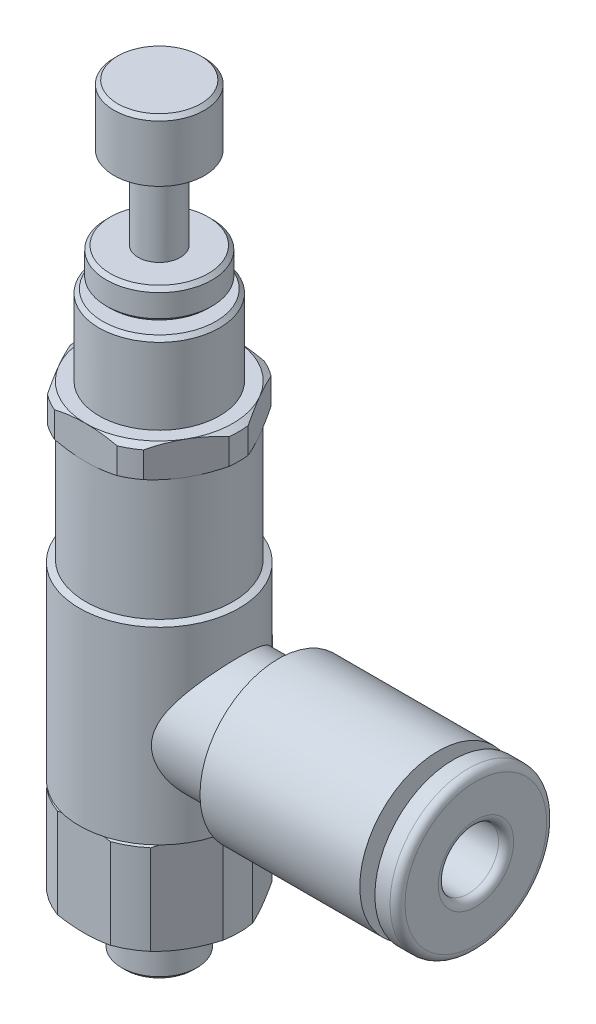
SolidWorks part; units mm, degrees
ref_plane "Front" through (0, 0, 0) normal (0, 0, 1) x (1, 0, 0)
ref_plane "Top" through (0, 0, 0) normal (0, 1, 0) x (1, 0, 0)
ref_plane "Right" through (0, 0, 0) normal (1, 0, 0) x (0, 0, -1)
ref_plane "K" through (0, 17.2, 0) normal (0, 1, 0) x (-1, 0, 0)
ref_plane "H" through (0, -15.5, 0) normal (0, 1, 0) x (-1, 0, 0)
ref_plane "J" through (0, 34.5, 0) normal (0, 1, 0) x (-1, 0, 0)
ref_plane "A" through (21, 0, 0) normal (1, 0, 0) x (0, 0, -1)
ref_plane "G" through (0, -12, 0) normal (0, 1, 0) x (-1, 0, 0)
ref_plane "Nut Thickness" through (0, -5.7, 0) normal (0, 1, 0) x (-1, 0, 0)
sketch "MBody_Sketch" plane through (0, 0, 0) normal (0, 0, 1) x (1, 0, 0)
  line L0 (0, 0) -> (0, 81.026) construction
  line L1 (0, 17.2) -> (-4.875, 17.2)
  line L2 (-4.875, 17.2) -> (-4.875, 6.9547)
  line L3 (-4.875, 6.9547) -> (-5.3, 6.8)
  line L4 (-5.3, 6.8) -> (-5.3, -5.7)
  line L5 (-5.3, -5.7) -> (0, -5.7)
  line L6 (0, -5.7) -> (0, 17.2)
  line L7 (50, -5.7) -> (-50, -5.7) construction
  line L8 (50, 17.2) -> (-50, 17.2) construction
  dimension "Top Dia" = 9.75
  dimension "Bot Dia" = 10.6
  dimension "Loc Angle" = 12.5
  dimension "Angle" = 70
revolve "MBody" add sketch "MBody_Sketch" angle 360 about L0
sketch "Nut Top_Sketch" plane through (0, 17.2, 0) normal (0, 1, 0) x (-1, 0, 0)
  line L1 (-2.8146, 4.875) -> (-5.6292, 0)
  line L2 (-5.6292, 0) -> (-2.8146, -4.875)
  line L3 (-2.8146, -4.875) -> (2.8146, -4.875)
  line L4 (2.8146, -4.875) -> (5.6292, 0)
  line L5 (5.6292, 0) -> (2.8146, 4.875)
  line L6 (2.8146, 4.875) -> (-2.8146, 4.875)
  circle A0 centre (0, 0) radius 4.875 construction
  circle A1 centre (0, 0) radius 4.875 construction
  point P11 (-4.875, 0)
extrude "Nut Top" add sketch "Nut Top_Sketch" against normal blind 2.2
sketch "Nut Cham Top_Sketch" plane through (0, 0, 0) normal (0, 0, 1) x (1, 0, 0)
  line L0 (5.6292, 17.2) -> (4.875, 17.2)
  line L1 (4.875, 17.2) -> (5.6292, 16.7646)
  line L2 (5.6292, 15) -> (5.6292, 17.2) construction
  line L3 (5.6292, 16.7646) -> (5.6292, 17.2)
  line L5 (5.6292, 16.1) -> (29.5748, 16.1) construction
  line L6 (5.6292, 15.4354) -> (5.6292, 15)
  line L7 (4.875, 15) -> (5.6292, 15.4354)
  line L8 (5.6292, 15) -> (4.875, 15)
  line L9 (0, 0) -> (0, 22.8249) construction
  dimension "Angle" = 30
revolve "Nut Cham Top" cut sketch "Nut Cham Top_Sketch" angle 360 about L9
sketch "Nut Bot_Sketch" plane through (0, -5.7, 0) normal (0, -1, 0) x (1, 0, 0)
  line L1 (2.8868, -5) -> (5.7735, 0)
  line L2 (5.7735, 0) -> (2.8868, 5)
  line L3 (2.8868, 5) -> (-2.8868, 5)
  line L4 (-2.8868, 5) -> (-5.7735, 0)
  line L5 (-5.7735, 0) -> (-2.8868, -5)
  line L6 (-2.8868, -5) -> (2.8868, -5)
  circle A0 centre (0, 0) radius 5 construction
  point P1 (5, 0)
  dimension "F" = 10
extrude "Nut Bot" add sketch "Nut Bot_Sketch" along normal up to surface (6.3 mm away) up to plane "G"
sketch "Nut Cham Bot_Sketch" plane through (0, 0, 0) normal (0, 0, 1) x (1, 0, 0)
  line L0 (0, -2.2701) -> (0, -12.7985) construction
  line L1 (5.7735, -5.7) -> (5, -5.7)
  line L2 (5.7735, -12) -> (5.7735, -5.7) construction
  line L3 (5, -5.7) -> (5.7735, -6.1466)
  line L4 (5.7735, -6.1466) -> (5.7735, -5.7)
  line L5 (5.7735, -8.85) -> (-10.0496, -8.85) construction
  line L6 (5.7735, -11.5534) -> (5.7735, -12)
  line L7 (5, -12) -> (5.7735, -11.5534)
  line L8 (5.7735, -12) -> (5, -12)
  dimension "Angle" = 30
revolve "Nut Cham Bot" cut sketch "Nut Cham Bot_Sketch" angle 360 about L0
sketch "Nut Rounds_Sketch" plane through (0, -5.7, 0) normal (0, 1, 0) x (-1, 0, 0)
  circle A0 centre (0, 0) radius 5.3
  circle A1 centre (0, 0) radius 5.3 construction
extrude "Nut Rounds" cut sketch "Nut Rounds_Sketch" against normal through all and the other way through all flip side to cut
sketch "Threads_Sketch" plane through (0, -12, 0) normal (0, 1, 0) x (-1, 0, 0)
  circle A0 centre (0, 0) radius 2.5
  dimension "D" = 5
extrude "Threads" add sketch "Threads_Sketch" against normal up to surface (3.5 mm away) up to plane "H"
sketch "Threads MGT_Sketch" plane through (0, 17.2, 0) normal (0, 1, 0) x (-1, 0, 0)
  circle A0 centre (0, 0) radius 4
  dimension "Dia" = 8
extrude "Threads MGT" add sketch "Threads MGT_Sketch" along normal blind 5.3
sketch "Adjuster_Sketch" plane through (0, 0, 0) normal (0, 0, 1) x (1, 0, 0)
  line L0 (0, 0) -> (0, 38.6136) construction
  line L1 (0, -11.8268) -> (0, -5.8732) construction
  line L2 (0, 17.2) -> (0, 34.5)
  line L3 (0, 34.5) -> (3, 34.5)
  line L4 (3, 34.5) -> (3, 30.5)
  line L5 (3, 30.5) -> (1.4, 30.5)
  line L6 (1.4, 30.5) -> (1.4, 17.2)
  line L7 (1.4, 17.2) -> (0, 17.2)
  line L8 (50, 17.2) -> (-50, 17.2) construction
  line L10 (50, 34.5) -> (-50, 34.5) construction
  dimension "Height" = 4
  dimension "E" = 6
  dimension "Thread Dia" = 2.8
revolve "Adjuster" add sketch "Adjuster_Sketch" angle 360 about L0
sketch "Loc Spacer_Sketch" plane through (0, 22.5, 0) normal (0, 1, 0) x (-1, 0, 0)
  circle A0 centre (0, 0) radius 2
  dimension "Dia" = 4
extrude "Loc Spacer" add sketch "Loc Spacer_Sketch" along normal blind 0.5
sketch "Loc Adjuster_Sketch" plane through (0, 23, 0) normal (0, 1, 0) x (-1, 0, 0)
  circle A0 centre (0, 0) radius 3.5
  dimension "Dia" = 7
extrude "Loc Adjuster" add sketch "Loc Adjuster_Sketch" along normal blind 2
sketch "RBody_Sketch" plane through (0, 0, 0) normal (0, 0, 1) x (1, 0, 0)
  line L0 (0, 0) -> (35.732, 0) construction
  line L1 (0, 0) -> (0, 4)
  line L2 (0, -11.8268) -> (0, -5.8732) construction
  line L3 (0, 4) -> (7.4632, 4)
  line L4 (7.4632, 4) -> (7.9, 5.2)
  line L5 (7.9, 5.2) -> (18.5, 5.2)
  line L6 (18.5, 5.2) -> (18.5, 0)
  line L7 (18.5, 0) -> (0, 0)
  line L8 (21, -50) -> (21, 50) construction
  dimension "B" = 10.4
  dimension "Dist" = 2.5
  dimension "Length" = 10.6
  dimension "D4" = 70
  dimension "Dia" = 8
revolve "RBody" add sketch "RBody_Sketch" angle 360 about L0
sketch "Release_Sketch" plane through (0, 0, 0) normal (0, 0, 1) x (1, 0, 0)
  line L0 (0, 0) -> (30.7225, 0) construction
  line L1 (0, 0) -> (35.732, 0) construction
  line L2 (18.5, 0) -> (18.5, 2.75)
  line L3 (18.5, 2.75) -> (19.5, 2.75)
  line L4 (19.5, 2.75) -> (19.5, 5.2)
  line L5 (19.5, 5.2) -> (21, 5.2)
  line L6 (21, 5.2) -> (21, 0)
  line L7 (21, 0) -> (18.5, 0)
  line L8 (18.5, -5.2) -> (18.5, 5.2) construction
  line L9 (18.5, 5.2) -> (7.9, 5.2) construction
  line L10 (21, -50) -> (21, 50) construction
  dimension "Tube Dia" = 5.5
  dimension "Thickness" = 1.5
revolve "Release" add sketch "Release_Sketch" angle 360 about L0
sketch "Tube_Sketch" plane through (21, 0, 0) normal (1, 0, 0) x (0, 0, -1)
  circle A0 centre (0, 0) radius 2
  circle A1 centre (0, 0) radius 5.2 construction
  dimension "C" = 4
extrude "Tube" cut sketch "Tube_Sketch" against normal blind 13
fillet "Tube Rouds" radius 0.5 2 edges at (21, 0, 5.2) (21, 0, -2)
sketch "Path Port" plane through (0, 0, 0) normal (0, 0, 1) x (1, 0, 0)
  line L0 (21, 0) -> (3, 0)
  line L1 (0, -3) -> (0, -15.5)
  line L2 (50, -15.5) -> (-50, -15.5) construction
  line L3 (21, -50) -> (21, 50) construction
  arc A0 (0, -3) -> (3, 0) centre (3, -3) cw
  point P10 (0, 0)
  dimension "Radius" = 3
sketch "Profile Port" plane through (21, 0, 0) normal (1, 0, 0) x (0, 0, -1)
  circle A0 centre (0, 0) radius 1.25
  dimension "Dia" = 2.5
sweep "Port" cut profiles "Profile Port" path "Path Port"
chamfer "Cham" distance 0.25 5 edges at (0, -15.5, 2.5) (0, 22.5, 4) (0, 34.5, -3) (0, 23, 3.5) (0, 25, 3.5)
